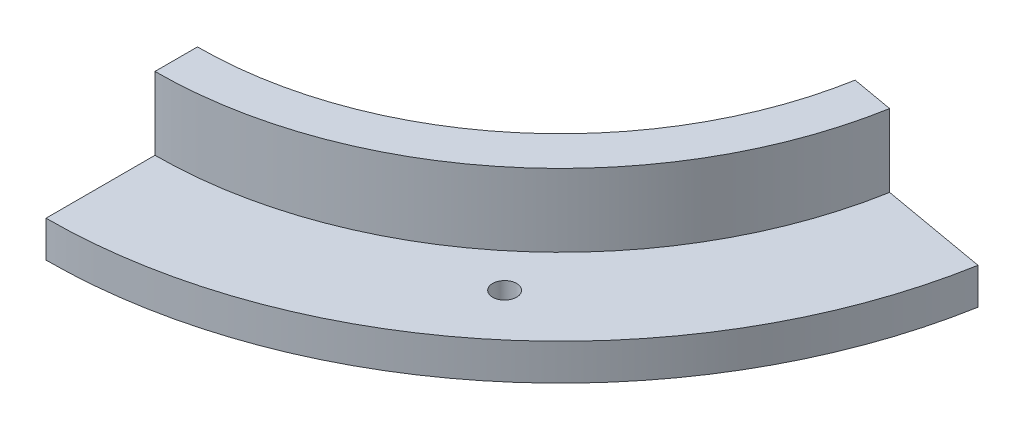
SolidWorks part; units mm, degrees
ref_plane "Piano frontale" through (0, 0, 0) normal (0, 0, 1) x (1, 0, 0)
ref_plane "Piano superiore" through (0, 0, 0) normal (0, 1, 0) x (1, 0, 0)
ref_plane "Piano destro" through (0, 0, 0) normal (1, 0, 0) x (0, 0, -1)
sketch "Schizzo1" plane through (0, 0, 0) normal (0, 1, 0) x (1, 0, 0)
  line L0 (0, 0) -> (0, -91.7) construction
  line L1 (0, -91.7) -> (0, -141.7)
  line L2 (50.9316, -76.2552) -> (66.2525, -63.3995)
  line L3 (90.3069, -15.9235) -> (139.5473, -24.6059)
  line L4 (0, 0) -> (90.3069, -15.9235) construction
  line L5 (58.5921, -69.8273) -> (0, 0) construction
  arc A0 (0, -91.7) -> (50.9316, -76.2552) centre (0, 0) ccw
  arc A1 (0, -141.7) -> (139.5473, -24.6059) centre (0, 0) ccw
  arc A2 (66.2525, -63.3995) -> (90.3069, -15.9235) centre (0, 0) ccw
  dimension "D1" = 183.4
  dimension "D3" = 50
  dimension "D2" = 80
  dimension "D4" = 20
  dimension "D5" = 40
extrude "Estrusione-Estrusione1" add sketch "Schizzo1" along normal blind 20
sketch "Schizzo2" plane through (0, 20, 0) normal (0, 1, 0) x (1, 0, 0)
  line L0 (0, -100) -> (0, -141.7)
  line L4 (98.4808, -17.3648) -> (139.5473, -24.6059)
  line L5 (139.5473, -24.6059) -> (90.3069, -15.9235) construction
  arc A0 (0, -100) -> (98.4808, -17.3648) centre (0, 0) ccw
  arc A1 (0, -141.7) -> (139.5473, -24.6059) centre (0, 0) ccw
  dimension "D1" = 200
extrude "Estrusione-Estrusione2" add sketch "Schizzo2" along normal blind 10
chamfer "Smusso1" [suppressed] distance 30 angle 45
sketch "Schizzo4" plane through (58.5921, 0, 69.8273) normal (-0.6428, 0, -0.766) x (-0.766, 0, 0.6428)
  line L0 (-10, 0) -> (10, 0) construction
  line L1 (10, 20) -> (10, 0) construction
  circle A0 centre (0, 10) radius 2.8
  dimension "D1" = 5.6
  dimension "D2" = 10
  dimension "D3" = 10
extrude "Taglio-Estrusione2" cut sketch "Schizzo4" against normal blind 2.8
sketch "Schizzo5" plane through (0, 30, 0) normal (0, 1, 0) x (1, 0, 0)
  line L0 (0, -141.7) -> (0, -111.7)
  line L1 (139.5473, -24.6059) -> (110.003, -19.3965)
  line L2 (139.5473, -24.6059) -> (98.4808, -17.3648) construction
  arc A0 (0, -141.7) -> (139.5473, -24.6059) centre (0, 0) ccw
  arc A1 (0, -111.7) -> (110.003, -19.3965) centre (0, 0) ccw
  dimension "D1" = 30
extrude "Taglio-Estrusione3" cut sketch "Schizzo5" against normal blind 20
hole_wizard "Foro per Vite M6-1" positions "Schizzo3D1" profile "Schizzo6" hole size "M6" standard "DIN" end condition through all
sketch3d "Schizzo3D1"
  line L0 (80.3485, 10, 95.7556) -> (0, 10, 0) construction
  line L1 (0, 10, 0) -> (0, 30, 0) construction
  line L5 (0, 10, 0) -> (0, 10, 141.7) construction
  line L9 (90.3069, 20, 15.9235) -> (0, 10, 0) construction
  arc A0 (110.003, 10, 19.3965) -> (0, 10, 111.7) centre (0, 10, 0) ccw construction
  point P0 (80.3485, 10, 95.7556)
  point P6 (0, -101.7, 0)
  dimension "D1" = 125
  dimension "D2" = 40
sketch "Schizzo6" plane through (80.3485, 10, 95.7556) normal (1, 0, 0) x (0, 0, 1)
  line L0 (0, 0) -> (0, 10)
  line L1 (0, 10) -> (3.3, 10)
  line L2 (3.3, 10) -> (3.3, 0)
  line L5 (3.3, 0) -> (0, 0)
  line L11 (0, -6.35) -> (0, 107.95) construction
  dimension "Thru Hole Dia." = 6.6
  dimension "Thru Hole Depth" = 10
